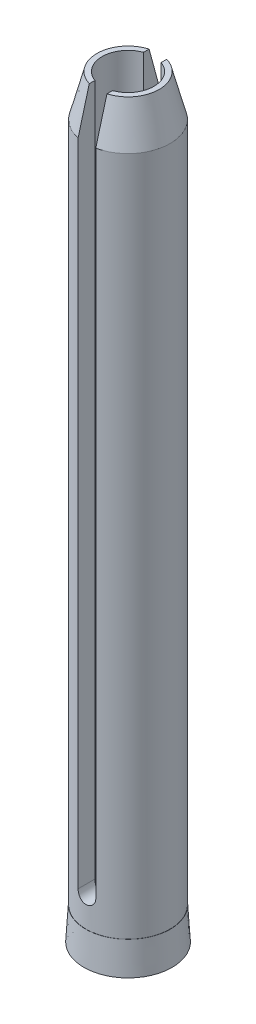
SolidWorks part; units mm, degrees
ref_plane "Alzado" through (0, 0, 0) normal (0, 0, 1) x (1, 0, 0)
ref_plane "Planta" through (0, 0, 0) normal (0, 1, 0) x (1, 0, 0)
ref_plane "Vista lateral" through (0, 0, 0) normal (1, 0, 0) x (0, 0, -1)
sketch "Croquis1" plane through (0, 0, 0) normal (0, 1, 0) x (1, 0, 0)
  circle A0 centre (0, 0) radius 8.24
  dimension "D1" = 16.48
extrude "Saliente-Extruir1" add sketch "Croquis1" along normal blind 6
sketch "Croquis2" plane through (0, 0, 0) normal (0, 0, 1) x (1, 0, 0)
  line L0 (-8.24, 0) -> (-7.8837, 6)
  line L1 (8.24, 6) -> (-8.24, 6) construction
  line L2 (-7.8837, 6) -> (-8.24, 6)
  line L3 (-8.24, 6) -> (-8.24, 0)
  line L4 (0, 0) -> (0, 8.527) construction
revolve "Cortar-Revolución1" cut sketch "Croquis2" angle 360 about L4
sketch "Croquis3" plane through (0, 6, 0) normal (0, 1, 0) x (1, 0, 0)
  circle A0 centre (0, 0) radius 7.85
  dimension "D1" = 15.7
extrude "Saliente-Extruir2" add sketch "Croquis3" along normal blind 134.8
sketch "Croquis4" plane through (0, 140.8, 0) normal (0, 1, 0) x (1, 0, 0)
  circle A0 centre (0, 0) radius 4.835
  dimension "D1" = 9.67
extrude "Cortar-Extruir1" cut sketch "Croquis4" against normal through all
sketch "Croquis5" plane through (0, 0, 0) normal (0, 0, 1) x (1, 0, 0)
  line L0 (0, 140.8) -> (0, 0) construction
  line L1 (4.835, 140.8) -> (-4.835, 140.8) construction
  line L2 (18.1672, 9.97) -> (-18.1672, 9.97) construction
  line L3 (7.8837, 6) -> (-7.8837, 6) construction
  line L4 (1.65, 140.8) -> (-1.65, 140.8)
  line L5 (-1.65, 140.8) -> (-1.65, 11.6214)
  line L6 (1.65, 140.8) -> (1.65, 11.6214)
  arc A0 (-1.65, 11.6214) -> (1.65, 11.6214) centre (0, 11.62) ccw
  point P8 (0, 9.97)
  point P13 (0, 140.8)
  point P16 (-1.65, 11.62)
  point P17 (-1.65, 11.62)
  dimension "D1" = 3.97
  dimension "D2" = 3.3
extrude "Cortar-Extruir2" cut sketch "Croquis5" against normal through all both and the other way through all
sketch "Croquis7" plane through (0, 0, 0) normal (0, 0, 1) x (1, 0, 0)
  line L0 (1.65, 140.8) -> (-1.65, 140.8) construction
  line L1 (0, 140.8) -> (0, 133.06) construction
  line L2 (0, 133.06) -> (11.6465, 133.06) construction
  line L3 (11.6465, 140.8) -> (7.85, 133.06)
  line L4 (7.85, 6) -> (7.85, 140.8) construction
  line L5 (7.85, 133.06) -> (5.8232, 140.8)
  line L6 (7.85, 140.8) -> (1.65, 140.8) construction
  line L7 (5.8232, 140.8) -> (11.6465, 140.8)
  point P12 (11.6465, 140.8)
  dimension "D1" = 7.74
revolve "Cortar-Revolución2" cut sketch "Croquis7" angle 360 about L1
sketch "Croquis8" plane through (0, 0, 0) normal (0, 1, 0) x (1, 0, 0)
  circle A0 centre (0, 0) radius 7.95
  circle A2 centre (0, 0) radius 4.835
  dimension "D1" = 15.9
  dimension "D2" = 3.115
